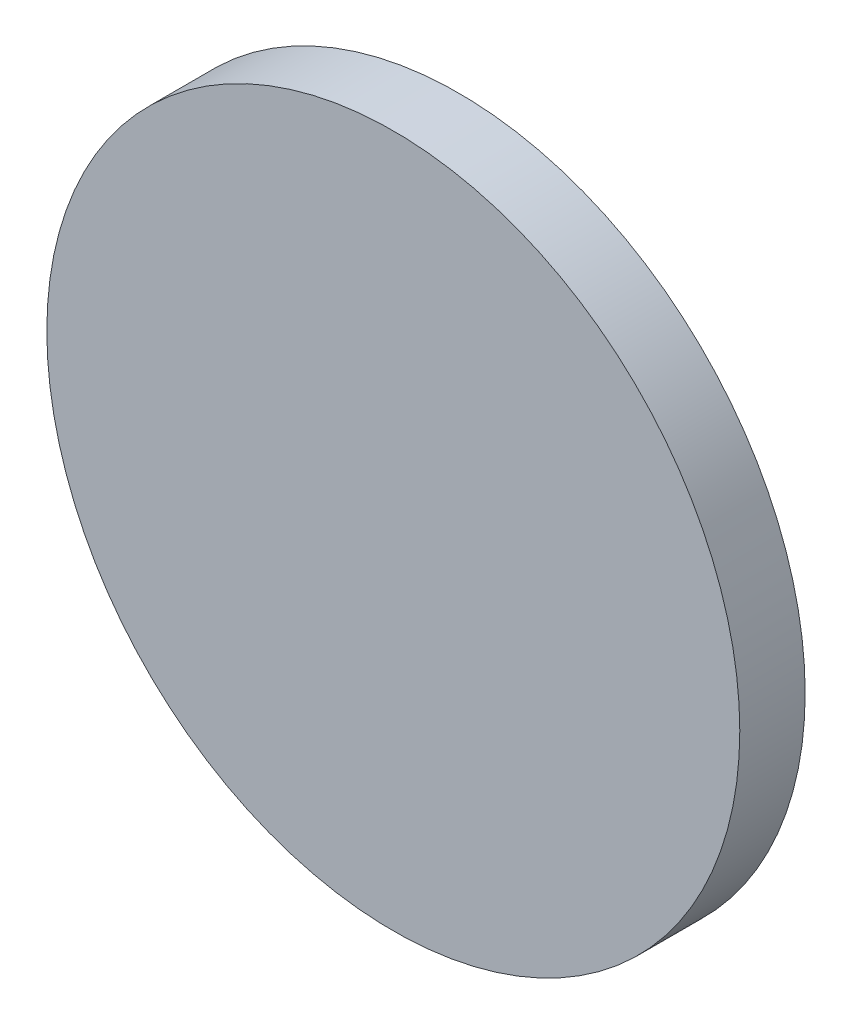
SolidWorks part; units mm, degrees
ref_plane "Front Plane" through (0, 0, 0) normal (0, 0, 1) x (1, 0, 0)
ref_plane "Top Plane" through (0, 0, 0) normal (0, 1, 0) x (1, 0, 0)
ref_plane "Right Plane" through (0, 0, 0) normal (1, 0, 0) x (0, 0, -1)
sketch "Sketch1" plane through (0, 0, 0) normal (0, 0, 1) x (1, 0, 0)
  circle A0 centre (0, 0) radius 1346.2
extrude "Boss-Extrude3" add sketch "Sketch1" along normal blind 254 contours A0
sketch "Sketch2" plane through (0, 0, 0) normal (0, 0, 1) x (1, 0, 0)
  line L1 (-635, -355.6) -> (635, -355.6)
  line L2 (-635, -355.6) -> (-635, 355.6)
  line L3 (-635, 355.6) -> (635, 355.6)
  line L4 (635, -355.6) -> (635, 355.6)
  line L5 (-635, -355.6) -> (635, 355.6) construction
  line L6 (-635, 355.6) -> (635, -355.6) construction
  circle A0 centre (965.2, 0) radius 254
  circle A1 centre (-965.2, 0) radius 254
  circle A2 centre (0, 965.2) radius 254
  point P6 (0, 0)
